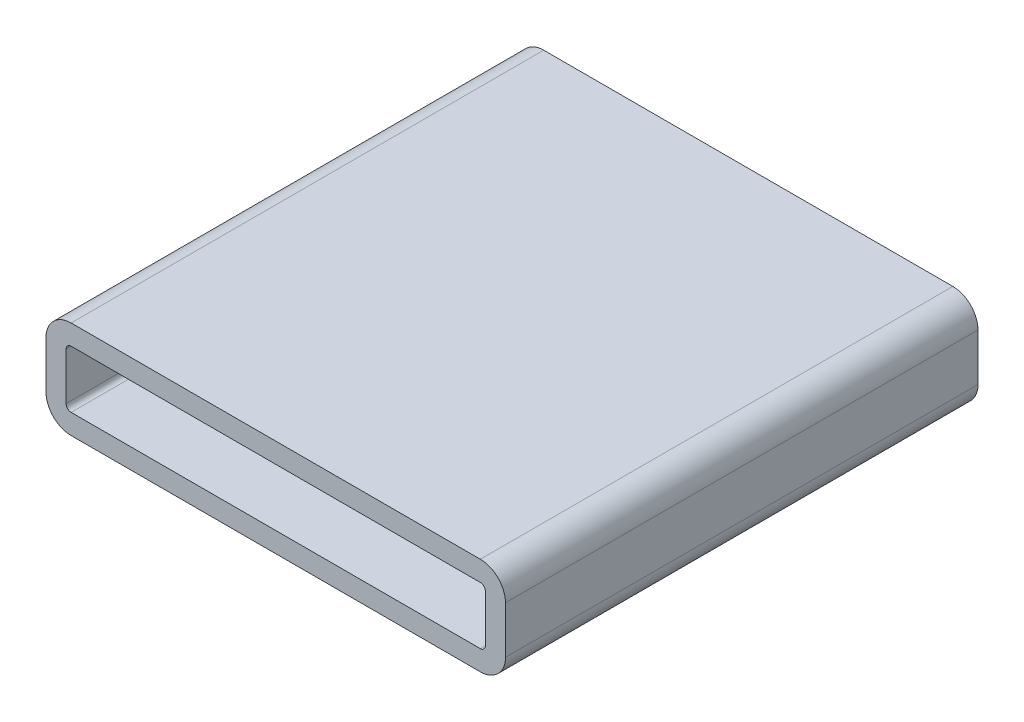
SolidWorks part; units mm, degrees
material "Copper"
ref_plane "Front Plane" through (0, 0, 0) normal (0, 0, 1) x (1, 0, 0)
ref_plane "Top Plane" through (0, 0, 0) normal (0, 1, 0) x (1, 0, 0)
ref_plane "Right Plane" through (0, 0, 0) normal (1, 0, 0) x (0, 0, -1)
sketch "Sketch1" plane through (0, 0, 0) normal (0, 0, 1) x (1, 0, 0)
  line L0 (-20.35, 4.85) -> (20.35, 4.85)
  line L1 (-20.35, -2.85) -> (20.35, -2.85)
  line L2 (-20.85, -2.35) -> (-20.85, 2.35)
  line L3 (-20.35, 2.85) -> (20.35, 2.85)
  line L4 (20.85, -2.35) -> (20.85, 2.35)
  line L5 (-20.85, -2.85) -> (20.85, 2.85) construction
  line L6 (-20.85, 2.85) -> (20.85, -2.85) construction
  line L7 (22.85, -2.35) -> (22.85, 2.35)
  line L8 (-20.35, -4.85) -> (20.35, -4.85)
  line L9 (-22.85, -2.35) -> (-22.85, 2.35)
  arc A0 (-20.35, -2.85) -> (-20.85, -2.35) centre (-20.35, -2.35) cw
  arc A1 (20.35, -2.85) -> (20.85, -2.35) centre (20.35, -2.35) ccw
  arc A2 (20.35, 2.85) -> (20.85, 2.35) centre (20.35, 2.35) cw
  arc A3 (-20.85, 2.35) -> (-20.35, 2.85) centre (-20.35, 2.35) cw
  arc A4 (20.35, 4.85) -> (22.85, 2.35) centre (20.35, 2.35) cw
  arc A5 (20.35, -4.85) -> (22.85, -2.35) centre (20.35, -2.35) ccw
  arc A6 (-20.35, -4.85) -> (-22.85, -2.35) centre (-20.35, -2.35) cw
  arc A7 (-22.85, 2.35) -> (-20.35, 4.85) centre (-20.35, 2.35) cw
  point P0 (0, 0)
  dimension "D3" = 0.5
  dimension "D1" = 5.7
  dimension "D2" = 41.7
  dimension "D4" = 2
extrude "Boss-Extrude1" add sketch "Sketch1" along normal blind 47
